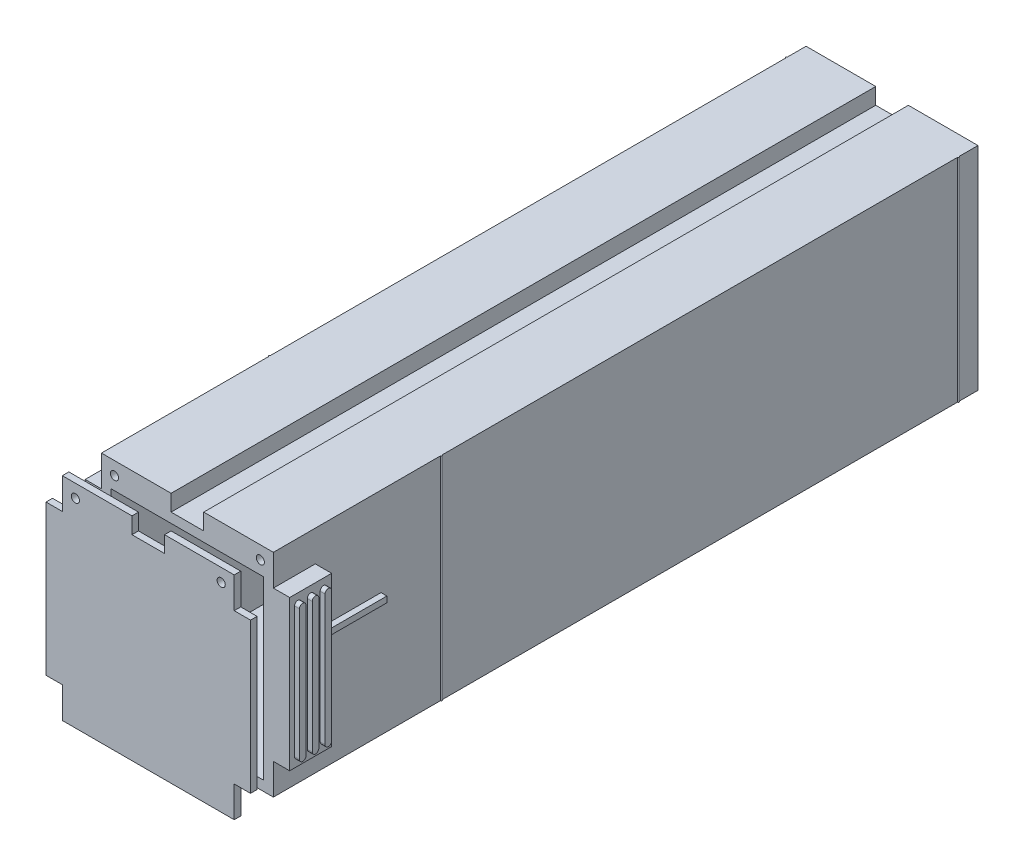
SolidWorks part; units mm, degrees
ref_plane "前视基准面" through (0, 0, 0) normal (0, 0, 1) x (1, 0, 0)
ref_plane "上视基准面" through (0, 0, 0) normal (0, 1, 0) x (1, 0, 0)
ref_plane "右视基准面" through (0, 0, 0) normal (1, 0, 0) x (0, 0, -1)
other "Configuration Table"
sketch "草图1" plane through (0, 0, 0) normal (0, 0, 1) x (1, 0, 0)
  line L1 (0, 0) -> (52.7, 0)
  line L2 (0, 0) -> (0, 65)
  line L3 (0, 65) -> (52.7, 65)
  line L4 (52.7, 0) -> (52.7, 65)
  line L5 (0, 0) -> (52.7, 65) construction
  line L6 (0, 65) -> (52.7, 0) construction
  point P4 (26.35, 32.5)
  dimension "D1" = 52.7
  dimension "D2" = 65
extrude "凸台-拉伸1" add sketch "草图1" along normal blind 216
sketch "草图2" plane through (0, 0, 216) normal (0, 0, 1) x (1, 0, 0)
  line L0 (26.35, 65) -> (26.35, 0) construction
  line L2 (21.35, 65) -> (31.35, 65)
  line L3 (21.35, 65) -> (21.35, 60)
  line L4 (0, 65) -> (0, 0)
  line L5 (0, 0) -> (52.7, 0)
  line L6 (52.7, 0) -> (52.7, 65)
  line L7 (52.7, 65) -> (0, 65)
  line L8 (0, 65) -> (0, 0) construction
  line L9 (0, 0) -> (52.7, 0) construction
  line L10 (52.7, 0) -> (52.7, 65) construction
  line L11 (52.7, 65) -> (0, 65) construction
  line L12 (21.35, 60) -> (31.35, 60)
  line L13 (31.35, 65) -> (31.35, 60)
  line L14 (21.35, 65) -> (31.35, 60) construction
  line L15 (21.35, 60) -> (31.35, 65) construction
  point P10 (26.35, 62.5)
  line M11 (52.7, 65) -> (0, 65)
  dimension "D2" = 5
  dimension "D3" = 10
  dimension "D1" = 0
extrude "切除-拉伸1" cut sketch "草图2" against normal through all contours L3 L12 L0 M11
sketch "草图3" plane through (0, 0, 216) normal (0, 0, 1) x (1, 0, 0)
  line L0 (0, 60) -> (52.7, 60) construction
  line L1 (3, 57) -> (49.7, 57)
  line L2 (49.7, 3) -> (49.7, 57)
  line L3 (3, 3) -> (49.7, 3)
  line L4 (3, 57) -> (3, 3)
  line L5 (31.35, 57) -> (21.35, 57)
  line L8 (31.35, 60) -> (21.35, 60)
  line L9 (21.35, 60) -> (21.35, 65)
  line L10 (21.35, 65) -> (0, 65)
  line L11 (0, 65) -> (0, 0)
  line L12 (0, 0) -> (52.7, 0)
  line L13 (52.7, 0) -> (52.7, 65)
  line L14 (52.7, 65) -> (31.35, 65)
  line L15 (31.35, 65) -> (31.35, 60)
  line L16 (31.35, 60) -> (21.35, 60)
  line L19 (0, 60) -> (0, 0) construction
  line L20 (0, 0) -> (52.7, 0) construction
  line L21 (52.7, 0) -> (52.7, 60) construction
  line L30 (31.35, 65) -> (31.35, 60)
  dimension "D1" = 0
  dimension "D2" = 3
extrude "切除-拉伸2" cut sketch "草图3" against normal offset from surface (211 mm away) 5 contours L1 L4 L3 L2 up to face at (26.35, 47.5, 0)
sketch "草图6" plane through (0, 0, 0) normal (0, 0, -1) x (-1, 0, 0)
  line L0 (-26.35, 60) -> (-26.35, 0) construction
  line L1 (-21.35, 60) -> (-31.35, 60) construction
  line L2 (0, 0) -> (-52.7, 0) construction
  line L3 (-40.6065, 14.2) -> (-11.5971, 14.2) construction
  line L4 (-34.35, 22.2) -> (-18.35, 22.2)
  line L5 (-34.35, 22.2) -> (-34.35, 6.2)
  line L6 (-34.35, 6.2) -> (-18.35, 6.2)
  line L7 (-18.35, 22.2) -> (-18.35, 6.2)
  line L8 (-34.35, 22.2) -> (-18.35, 6.2) construction
  line L9 (-34.35, 6.2) -> (-18.35, 22.2) construction
  line L10 (-39.1, 14.2) -> (-13.6, 14.2) construction
  line L15 (-3, 3) -> (-3, 57)
  line L16 (-49.7, 3) -> (-3, 3)
  line L17 (-49.7, 57) -> (-49.7, 3)
  line L18 (-3, 57) -> (-49.7, 57)
  line L19 (-3, 3) -> (-3, 57) construction
  line L20 (-49.7, 3) -> (-3, 3) construction
  line L21 (-49.7, 57) -> (-49.7, 3) construction
  line L22 (-3, 57) -> (-49.7, 57) construction
  circle A0 centre (-13.6, 14.2) radius 1.75
  circle A1 centre (-39.1, 14.2) radius 1.75
  point P10 (-26.35, 14.2)
  point P17 (-26.35, 14.2)
  dimension "D5" = 3.5
  dimension "D6" = 3.5
  dimension "D1" = 3.2
  dimension "D2" = 16
  dimension "D3" = 0
  dimension "D4" = 16
  dimension "D7" = 25.5
  dimension "D8" = 0
extrude "切除-拉伸3" cut sketch "草图6" against normal offset from surface (5 mm away) 5 up to face at (26.35, 47.5, 0)
sketch "草图7" plane through (0, 0, 216) normal (0, 0, 1) x (1, 0, 0)
  line L0 (52.7, 0) -> (52.7, 65) construction
  line L1 (52.7, 36) -> (54.5, 36)
  line L2 (52.7, 36) -> (52.7, 37.8)
  line L3 (52.7, 37.8) -> (54.5, 37.8)
  line L4 (54.5, 36) -> (54.5, 37.8)
  line L5 (52.7, 36) -> (54.5, 37.8) construction
  line L6 (52.7, 37.8) -> (54.5, 36) construction
  line L7 (52.7, 65) -> (31.35, 65) construction
  point P4 (53.6, 36.9)
  dimension "D1" = 29
  dimension "D2" = 1.8
  dimension "D3" = 1.8
extrude "凸台-拉伸2" add sketch "草图7" against normal blind 33
sketch "草图9" plane through (0, 0, 0) normal (-1, 0, 0) x (0, 0, 1)
  line L0 (218, 32.5) -> (0, 32.5) construction
  line L3 (216, 65) -> (216, 0) construction
  line L4 (216, 55.5) -> (203.15, 55.5)
  line L5 (216, 55.5) -> (216, 9.5)
  line L6 (216, 9.5) -> (203.15, 9.5)
  line L7 (203.15, 55.5) -> (203.15, 9.5)
  line L8 (216, 55.5) -> (203.15, 9.5) construction
  line L9 (216, 9.5) -> (203.15, 55.5) construction
  point P5 (209.575, 32.5)
  point P9 (0, 0)
  dimension "D1" = 12.85
  dimension "D2" = 46
extrude "凸台-拉伸3" add sketch "草图9" along normal blind 5
sketch "草图10" plane through (52.7, 0, 0) normal (1, 0, 0) x (0, 0, -1)
  line L4 (-203.15, 55.5) -> (-216, 55.5)
  line L5 (-203.15, 9.5) -> (-203.15, 55.5)
  line L6 (-216, 9.5) -> (-203.15, 9.5)
  line L7 (-216, 55.5) -> (-216, 9.5)
  line L8 (-203.15, 55.5) -> (-216, 55.5)
  line L9 (-203.15, 9.5) -> (-203.15, 55.5)
  line L10 (-216, 9.5) -> (-203.15, 9.5)
  line L11 (-216, 55.5) -> (-216, 9.5)
  dimension "D1" = 0
extrude "凸台-拉伸4" add sketch "草图10" along normal blind 5
sketch "草图11" plane through (57.7, 0, 0) normal (1, 0, 0) x (0, 0, -1)
  line L0 (-216, 32.5) -> (-203.15, 32.5) construction
  line L1 (-216, 55.5) -> (-216, 9.5) construction
  line L2 (-203.15, 9.5) -> (-203.15, 55.5) construction
  line L3 (-213.5, 12.5) -> (-213.5, 52.5) construction
  line L4 (-214.5, 12.5) -> (-214.5, 52.5)
  line L5 (-212.5, 12.5) -> (-212.5, 52.5)
  line L6 (-209.575, 12.5) -> (-209.575, 52.5) construction
  line L7 (-210.575, 12.5) -> (-210.575, 52.5)
  line L8 (-208.575, 12.5) -> (-208.575, 52.5)
  line L9 (-205.65, 12.5) -> (-205.65, 52.5) construction
  line L10 (-206.65, 12.5) -> (-206.65, 52.5)
  line L11 (-204.65, 12.5) -> (-204.65, 52.5)
  line L12 (-203.15, 37.8) -> (-203.15, 55.5) construction
  arc A0 (-214.5, 12.5) -> (-212.5, 12.5) centre (-213.5, 12.5) ccw
  arc A1 (-212.5, 52.5) -> (-214.5, 52.5) centre (-213.5, 52.5) ccw
  arc A2 (-210.575, 12.5) -> (-208.575, 12.5) centre (-209.575, 12.5) ccw
  arc A3 (-208.575, 52.5) -> (-210.575, 52.5) centre (-209.575, 52.5) ccw
  arc A4 (-206.65, 12.5) -> (-204.65, 12.5) centre (-205.65, 12.5) ccw
  arc A5 (-204.65, 52.5) -> (-206.65, 52.5) centre (-205.65, 52.5) ccw
  point P8 (-213.5, 32.5)
  point P14 (-209.575, 32.5)
  point P21 (-205.65, 32.5)
  dimension "D1" = 40
  dimension "D2" = 2
  dimension "D3" = 2.5
  dimension "D4" = 2.5
extrude "凸台-拉伸5" add sketch "草图11" along normal blind 1.5
sketch "草图12" plane through (-5, 0, 0) normal (-1, 0, 0) x (0, 0, 1)
  line L2 (214.5, 12.5) -> (214.5, 52.5)
  line L3 (212.5, 52.5) -> (212.5, 12.5)
  line L4 (214.5, 12.5) -> (214.5, 52.5)
  line L5 (212.5, 52.5) -> (212.5, 12.5)
  line L6 (206.65, 12.5) -> (206.65, 52.5)
  line L7 (204.65, 52.5) -> (204.65, 12.5)
  line L8 (206.65, 12.5) -> (206.65, 52.5)
  line L9 (204.65, 52.5) -> (204.65, 12.5)
  line L10 (210.575, 12.5) -> (210.575, 52.5)
  line L11 (208.575, 52.5) -> (208.575, 12.5)
  line L12 (210.575, 12.5) -> (210.575, 52.5)
  line L13 (208.575, 52.5) -> (208.575, 12.5)
  arc A2 (214.5, 52.5) -> (212.5, 52.5) centre (213.5, 52.5) ccw
  arc A3 (212.5, 12.5) -> (214.5, 12.5) centre (213.5, 12.5) ccw
  arc A4 (214.5, 52.5) -> (212.5, 52.5) centre (213.5, 52.5) ccw
  arc A5 (212.5, 12.5) -> (214.5, 12.5) centre (213.5, 12.5) ccw
  arc A6 (206.65, 52.5) -> (204.65, 52.5) centre (205.65, 52.5) ccw
  arc A7 (204.65, 12.5) -> (206.65, 12.5) centre (205.65, 12.5) ccw
  arc A8 (206.65, 52.5) -> (204.65, 52.5) centre (205.65, 52.5) ccw
  arc A9 (204.65, 12.5) -> (206.65, 12.5) centre (205.65, 12.5) ccw
  arc A10 (210.575, 52.5) -> (208.575, 52.5) centre (209.575, 52.5) ccw
  arc A11 (208.575, 12.5) -> (210.575, 12.5) centre (209.575, 12.5) ccw
  arc A12 (210.575, 52.5) -> (208.575, 52.5) centre (209.575, 52.5) ccw
  arc A13 (208.575, 12.5) -> (210.575, 12.5) centre (209.575, 12.5) ccw
  dimension "D1" = 0
  dimension "D2" = 0
  dimension "D3" = 0
extrude "凸台-拉伸6" add sketch "草图12" along normal blind 1.5
ref_plane "基准面1" through (0, 0, 226) normal (0, 0, 1) x (1, 0, 0)
sketch "草图14" plane through (0, 0, 226) normal (0, 0, 1) x (1, 0, 0)
  line L4 (3, 57) -> (3, 3)
  line L5 (3, 3) -> (49.7, 3)
  line L6 (49.7, 3) -> (49.7, 57)
  line L7 (49.7, 57) -> (3, 57)
  line L8 (3, 57) -> (3, 3) construction
  line L9 (3, 3) -> (49.7, 3) construction
  line L10 (49.7, 3) -> (49.7, 57) construction
  line L11 (49.7, 57) -> (3, 57) construction
  line L16 (57.7, 55.5) -> (52.7, 55.5)
  line L17 (52.7, 55.5) -> (52.7, 65)
  line L18 (52.7, 65) -> (31.35, 65)
  line L19 (31.35, 65) -> (31.35, 60)
  line L20 (31.35, 60) -> (21.35, 60)
  line L21 (21.35, 60) -> (21.35, 65)
  line L22 (21.35, 65) -> (0, 65)
  line L23 (0, 65) -> (0, 55.5)
  line L24 (0, 55.5) -> (-5, 55.5)
  line L25 (-5, 55.5) -> (-5, 9.5)
  line L26 (-5, 9.5) -> (0, 9.5)
  line L27 (0, 9.5) -> (0, 0)
  line L28 (0, 0) -> (52.7, 0)
  line L29 (52.7, 0) -> (52.7, 9.5)
  line L30 (52.7, 9.5) -> (57.7, 9.5)
  line L31 (57.7, 9.5) -> (57.7, 55.5)
  line L32 (57.7, 55.5) -> (52.7, 55.5)
  line L33 (52.7, 55.5) -> (52.7, 65)
  line L34 (52.7, 65) -> (31.35, 65)
  line L35 (31.35, 65) -> (31.35, 60)
  line L36 (31.35, 60) -> (21.35, 60)
  line L37 (21.35, 60) -> (21.35, 65)
  line L38 (21.35, 65) -> (0, 65)
  line L39 (0, 65) -> (0, 55.5)
  line L40 (0, 55.5) -> (-5, 55.5)
  line L41 (-5, 55.5) -> (-5, 9.5)
  line L42 (-5, 9.5) -> (0, 9.5)
  line L43 (0, 9.5) -> (0, 0)
  line L44 (0, 0) -> (52.7, 0)
  line L45 (52.7, 0) -> (52.7, 9.5)
  line L46 (52.7, 9.5) -> (57.7, 9.5)
  line L47 (57.7, 9.5) -> (57.7, 55.5)
  dimension "D1" = 0
  dimension "D2" = 0
extrude "凸台-拉伸7" add sketch "草图14" along normal blind 2 separate body
sketch "草图15" plane through (0, 0, 228) normal (0, 0, 1) x (1, 0, 0)
  line L0 (21.35, 65) -> (0, 65) construction
  line L1 (0, 65) -> (0, 55.5) construction
  line L2 (52.7, 65) -> (31.35, 65) construction
  line L3 (52.7, 55.5) -> (52.7, 65) construction
  circle A0 centre (4, 61) radius 1.25
  circle A1 centre (48.7, 61) radius 1.25
  point P12 (63.9114, 70.1382)
  dimension "D1" = 2.5
  dimension "D2" = 2.5
  dimension "D3" = 4
  dimension "D4" = 4
  dimension "D5" = 4
  dimension "D6" = 4
extrude "切除-拉伸4" cut sketch "草图15" against normal blind 20
sketch "草图18" plane through (0, 0, 0) normal (0, -1, 0) x (1, 0, 0)
  line L0 (0, 6) -> (52.7, 6) construction
  line L1 (0, 216) -> (0, 0) construction
  line L2 (52.7, 216) -> (52.7, 0) construction
  line L3 (0, 216) -> (52.7, 216) construction
  line L4 (0, 164.5) -> (52.7, 164.5) construction
  circle A0 centre (0, 6) radius 0.24
  circle A1 centre (52.7, 6) radius 0.24
  circle A2 centre (0, 164.5) radius 0.24
  circle A3 centre (52.7, 164.5) radius 0.24
  dimension "D1" = 0.48
  dimension "D2" = 0.48
  dimension "D4" = 0.48
  dimension "D5" = 0.48
  dimension "D3" = 210
  dimension "D6" = 51.5
extrude "凸台-拉伸8" add sketch "草图18" against normal up to surface (65 mm away) up to face at (10.675, 65, 108)
